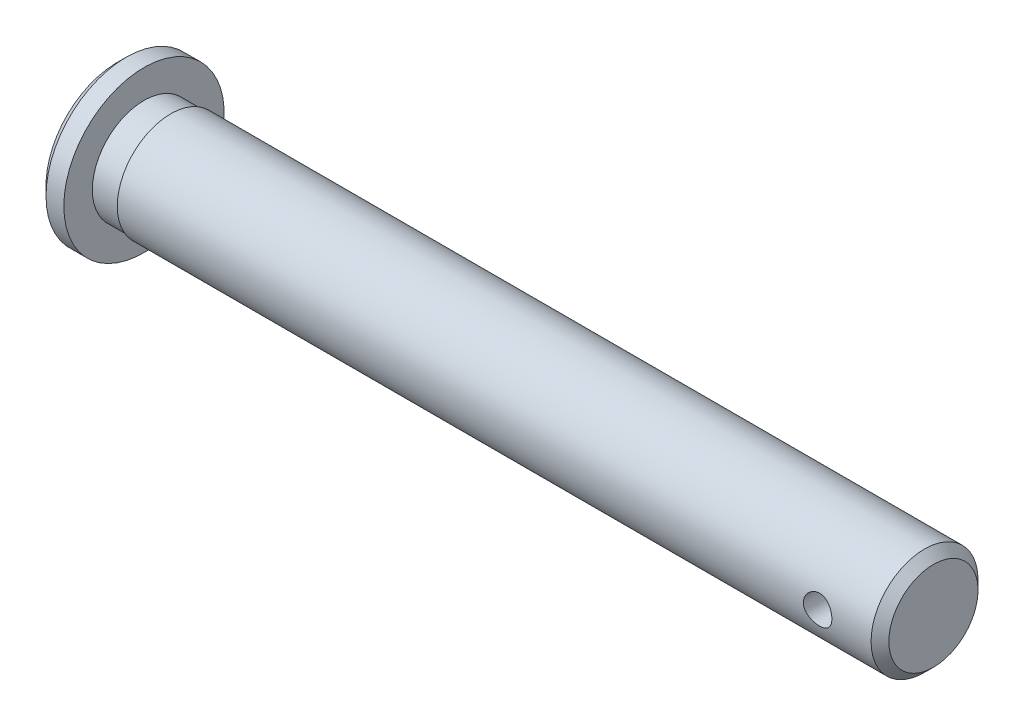
SolidWorks part; units mm, degrees
ref_plane "Front Plane" through (0, 0, 0) normal (0, 0, 1) x (1, 0, 0)
ref_plane "Top Plane" through (0, 0, 0) normal (0, 1, 0) x (1, 0, 0)
ref_plane "Right Plane" through (0, 0, 0) normal (1, 0, 0) x (0, 0, -1)
sketch "Sketch1" plane through (0, 0, 0) normal (0, 0, 1) x (1, 0, 0)
  line L0 (0, 0) -> (44.3, 0) construction
  line L1 (-1.5, 0) -> (-1.5, 4.5)
  line L2 (-1.5, 4.5) -> (0, 4.5)
  line L3 (0, 4.5) -> (0, 2.9)
  line L4 (0, 2.9) -> (1.5, 2.9)
  line L5 (44.3, 3) -> (44.3, 0)
  line L6 (44.3, 0) -> (-1.5, 0)
  line L7 (1.5, 2.9) -> (1.5, 3)
  line L8 (1.5, 3) -> (44.3, 3)
  line L9 (40, 3) -> (40, 0) construction
  line L10 (40.8, 0) -> (40.8, 3) construction
  point P2 (40.8, 0)
  dimension "D1" = 0.8
  dimension "L" = 40
  dimension "H" = 9
  dimension "T" = 1.5
  dimension "L1_1" = 45.8
  dimension "N_s" = 1.5
  dimension "U_s" = 5.8
  dimension "N" = 3.5
  dimension "D" = 6
revolve "Revolve1" add sketch "Sketch1" angle 360 about L0
ref_plane "Plane1" through (0, 0, 3) normal (0, 0, 1) x (1, 0, 0)
sketch "Sketch2" plane through (0, 0, 3) normal (0, 0, 1) x (1, 0, 0)
  line L2 (44.3, -3) -> (44.3, 3) construction
  circle A0 centre (40.8, 0) radius 0.8
  point P5 (40, 0)
  dimension "D_s" = 1.6
  dimension "N" = 3.5
extrude "Cut-Extrude1" cut sketch "Sketch2" against normal through all
chamfer "Chamfer1" distance 0.5 angle 45 2 edges at (44.3, 0, 3) (-1.5, 0, 4.5)
sketch "Sketch3" [suppressed] plane through (0, 0, 0) normal (0, 0, 1) x (1, 0, 0)
  line L0 (-1.5, 0) -> (12.9, 0) construction
  line L1 (-1.5, 2.25) -> (-1.5, -2.25) construction
  line L2 (12.9, -1) -> (12.9, 1) construction
  line L3 (0, -2.75) -> (0, 2.75) construction
  line L4 (12.9, 0) -> (0, 0)
  line L5 (12.9, 0) -> (12.9, 1.5)
  line L6 (12.9, 1.5) -> (0, 1.5)
  line L7 (0, 0) -> (0, 1.5)
  dimension "D" = 6
revolve "Cut-Revolve2" [suppressed] cut sketch "Sketch3" angle 360 about L0
sketch "Sketch4" [suppressed] plane through (0, 0, 0) normal (0, 0, 1) x (1, 0, 0)
  line L0 (-1.5, 0) -> (11.9, 0) construction
  line L1 (-1.5, 2.25) -> (-1.5, -2.25) construction
  line L3 (1.5, 1.5) -> (1.5, 1.45)
  line L4 (0, 0) -> (11.9, 0)
  line L5 (0, 0) -> (0, 1.45)
  line L6 (1.5, 1.5) -> (11.9, 1.5)
  line L7 (11.9, 0) -> (11.9, 1.5)
  line L8 (1.5, 1.45) -> (0, 1.45)
  line L9 (10.4, 1.5) -> (10.4, 0) construction
  line L10 (10, 1.5) -> (10, 0) construction
  line L11 (0, -2.75) -> (0, 2.75) construction
  dimension "D1" = 0.8
  dimension "L" = 40
  dimension "N_s" = 1.5
  dimension "U_s" = 5.8
  dimension "L1_2" = 13.4
  dimension "NC" = 1.5
  dimension "D" = 6
revolve "Revolve2" [suppressed] add sketch "Sketch4" angle 360 about L0
sketch "Sketch5" [suppressed] plane through (0, 0, 1.5) normal (0, 0, 1) x (1, 0, 0)
  line L0 (0, 0) -> (11.9, 0) construction
  line L3 (11.9, -1.5) -> (11.9, 1.5) construction
  circle A0 centre (10.4, 0) radius 0.4
  dimension "D_s" = 1.6
  dimension "NC" = 1.5
extrude "Cut-Extrude2" [suppressed] cut sketch "Sketch5" against normal through all
chamfer "Chamfer2" [suppressed] distance 0.5 angle 45
sketch "Sketch6" [suppressed] plane through (0, 0, 0) normal (0, 0, 1) x (1, 0, 0)
  line L0 (-1.5, 2.25) -> (-1.5, -2.25) construction
  line L1 (-1.5, 2.75) -> (0, 2.75)
  line L2 (-1.5, 2.75) -> (-1.5, 0)
  line L3 (-1.5, 0) -> (0, 0)
  line L4 (0, 2.75) -> (0, 0)
  line L6 (0, -2.75) -> (0, 2.75) construction
  line L7 (0, 0) -> (-1.5, 0) construction
  dimension "H" = 9
revolve "Cut-Revolve3" [suppressed] cut sketch "Sketch6" angle 360 about L7
sketch "Sketch7" [suppressed] plane through (0, 0, 0) normal (0, 0, 1) x (1, 0, 0)
  line L1 (-2, 2.75) -> (0, 2.75)
  line L2 (-2, 2.75) -> (-2, 0)
  line L3 (-2, 0) -> (0, 0)
  line L4 (0, 2.75) -> (0, 0)
  line L5 (0, 1.45) -> (0, -1.45) construction
  line L7 (0, 0) -> (-2, 0) construction
  line L8 (12.9, -1) -> (12.9, 1) construction
  dimension "H" = 9
  dimension "L1_3" = 14.9
  dimension "TC" = 2
revolve "Revolve3" [suppressed] add sketch "Sketch7" angle 360 about L7
chamfer "Chamfer3" [suppressed] distance 0.5 angle 45
sketch "Sketch8" [suppressed] plane through (0, 0, 0) normal (0, 0, 1) x (1, 0, 0)
  line L0 (0, 1.45) -> (0, -1.45) construction
  line L1 (-2, 2.75) -> (0, 2.75)
  line L2 (-2, 2.75) -> (-2, 0)
  line L3 (-2, 0) -> (0, 0)
  line L4 (0, 2.75) -> (0, 0)
  line L5 (11.9, -1) -> (11.9, 1) construction
  line L7 (0, 0) -> (-2, 0) construction
  dimension "H" = 9
  dimension "L1_4" = 13.9
  dimension "TC" = 2
revolve "Revolve5" [suppressed] add sketch "Sketch8" angle 360 about L7
chamfer "Chamfer4" [suppressed] distance 0.5 angle 45
sketch "Sketch9" [suppressed] plane through (0, 0, 0) normal (1, 0, 0) x (0, 0, -1)
  line L0 (0, 0) -> (-2.75, 0) construction
  line L1 (-2.75, 2.75) -> (-1.75, 2.75)
  line L2 (-2.75, 2.75) -> (-2.75, -2.75)
  line L3 (-2.75, -2.75) -> (-1.75, -2.75)
  line L4 (-1.75, 2.75) -> (-1.75, -2.75)
  dimension "D2" = 4.5
  dimension "HC" = 3.5
  dimension "H" = 9
extrude "Cut-Extrude3" [suppressed] cut sketch "Sketch9" against normal through all
equation "\"Plane dim\"= \"D@Sketch1\" * 0.5"
equation "\"D1@Sketch4\" = \"D_s@Sketch2\" / 2"
equation "\"HC@Sketch9\"=if ( \"D@Sketch1\" > 10 , \"H@Sketch1\" / 2 - 2 , \"H@Sketch1\" / 2 - 1 )"
equation "\"D2@Sketch9\"=\"H@Sketch1\"/2"
equation "\"D1@Sketch1\"=\"D_s@Sketch2\"/2"
